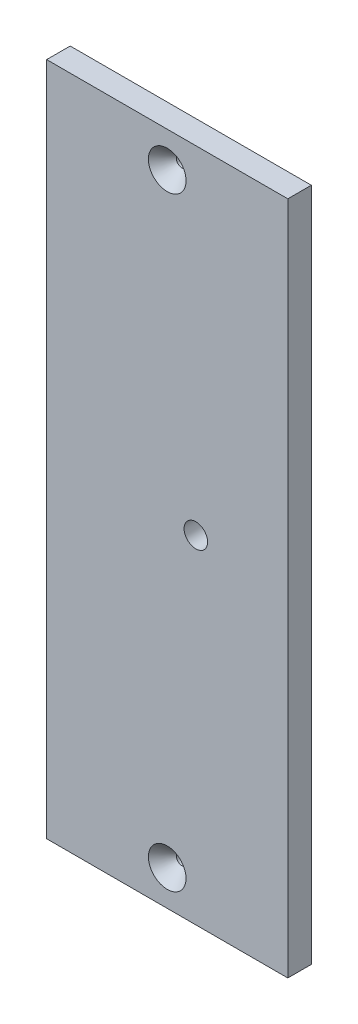
SolidWorks part; units mm, degrees
material "Beech"
ref_plane "Front Plane" through (0, 0, 0) normal (0, 0, 1) x (1, 0, 0)
ref_plane "Top Plane" through (0, 0, 0) normal (0, 1, 0) x (1, 0, 0)
ref_plane "Right Plane" through (0, 0, 0) normal (1, 0, 0) x (0, 0, -1)
sketch "Sketch1" plane through (0, 0, 0) normal (0, 0, 1) x (1, 0, 0)
  line L1 (-234.753, 19.05) -> (-299.8408, 19.05)
  line L2 (-234.753, 19.05) -> (-234.753, -163.1)
  line L3 (-234.753, -163.1) -> (-299.8408, -163.1)
  line L4 (-299.8408, 19.05) -> (-299.8408, -163.1)
  line L5 (-234.753, -163.1) -> (-350.6408, -163.1) construction
  point P5 (-299.8408, 19.05)
extrude "Boss-Extrude1" add sketch "Sketch1" along normal blind 6.35 contours L4 L3 L2 L1
hole_wizard "1/4 (0.25) Diameter Hole1" positions "Sketch4" profile "Sketch5" hole size "1/4" standard "ANSI Inch" end condition through all
sketch "Sketch4" plane through (0, 0, 6.35) normal (0, 0, 1) x (1, 0, 0)
  point P0 (-259.5764, -72.025)
  point P5 (-259.5764, -72.025)
sketch "Sketch5" plane through (-259.5764, -72.025, 6.35) normal (1, 0, 0) x (0, -1, 0)
  line L0 (0, 0) -> (0, 6.35)
  line L1 (0, 6.35) -> (3.175, 6.35)
  line L2 (3.175, 6.35) -> (3.175, 0)
  line L5 (3.175, 0) -> (0, 0)
  line L11 (0, -6.35) -> (0, 107.95) construction
  dimension "Thru Hole Dia." = 6.35
  dimension "Thru Hole Depth" = 6.35
hole_wizard "Hole1" positions "Sketch6" profile "Sketch7" legacy
sketch "Sketch6" plane through (181.0394, -72.025, 6.35) normal (0, 0, 1) x (0, 1, 0)
  line L0 (91.075, 448.3363) -> (-91.075, 448.3363) construction
  point P0 (81.55, 448.3363)
  point P2 (-81.55, 448.3363)
sketch "Sketch7" plane through (-267.2969, 9.525, 6.35) normal (1, 0, 0) x (0, -1, 0)
  line L0 (0, 0) -> (0, 32.7039)
  line L1 (0, 32.7039) -> (1.5875, 31.75)
  line L2 (1.5875, 31.75) -> (1.5875, 4.0177)
  line L3 (1.5875, 4.0177) -> (5.08, 0)
  line L4 (5.08, 0) -> (0, 0)
  line L5 (0, -14.3089) -> (0, 102.4216) construction
  line L6 (0, 32.7039) -> (-1.5875, 31.75) construction
  line L7 (-1.5875, 4.0177) -> (-5.08, 0) construction
  dimension "Diameter" = 3.175
  dimension "Depth" = 31.75
  dimension "C-Sink Diameter" = 10.16
  dimension "C-Sink Angle" = 82
  dimension "Drill Angle" = 118
